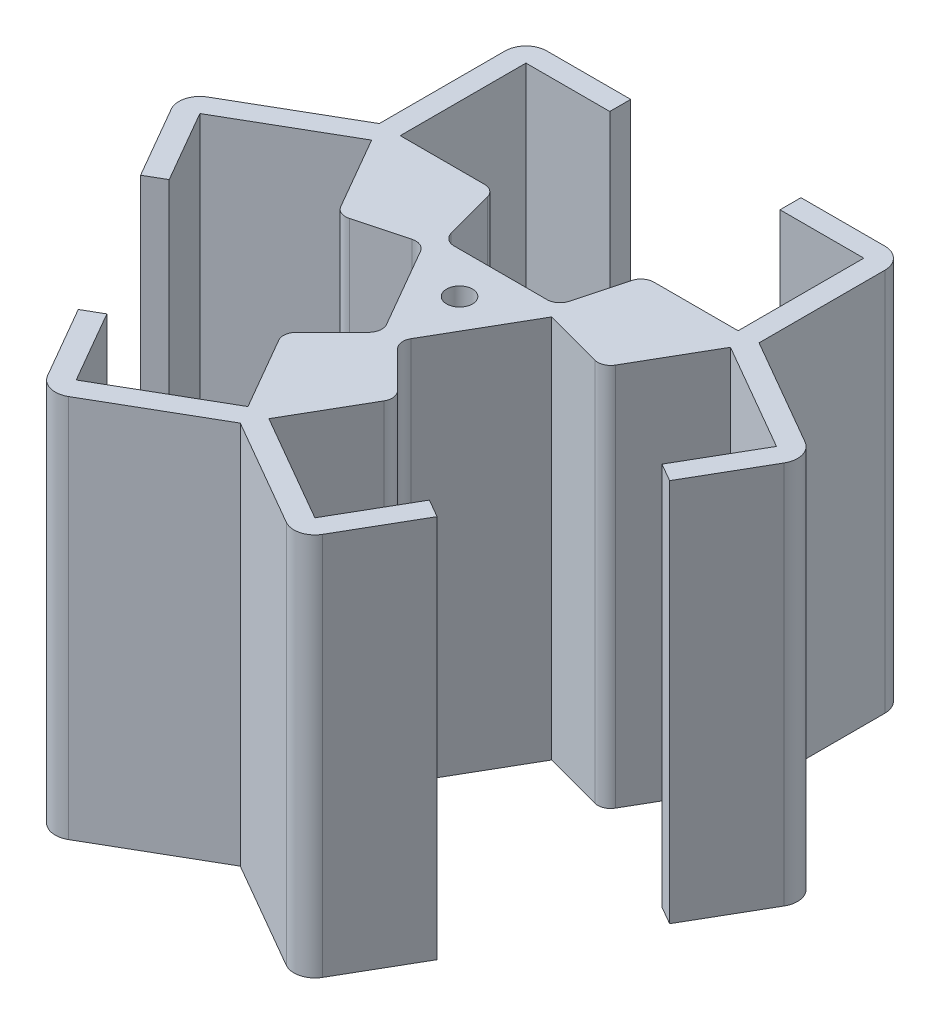
SolidWorks part; units mm, degrees
ref_plane "Alzado" through (0, 0, 0) normal (0, 0, 1) x (1, 0, 0)
ref_plane "Planta" through (0, 0, 0) normal (0, 1, 0) x (1, 0, 0)
ref_plane "Vista lateral" through (0, 0, 0) normal (1, 0, 0) x (0, 0, -1)
sketch "Croquis1" plane through (0, 0, 0) normal (0, 1, 0) x (1, 0, 0)
  line L0 (0, 50.8) -> (0, -50.8) construction
  line L1 (-50.8, 0) -> (50.8, 0) construction
  line L2 (0, 0) -> (-35.921, -35.921) construction
  line L3 (0, 0) -> (35.921, -35.921) construction
  line L10 (0, -17.5) -> (-15.1554, 8.75) construction
  line L11 (-15.1554, 8.75) -> (15.1554, 8.75) construction
  line L12 (15.1554, 8.75) -> (0, -17.5) construction
  line L13 (-1.2978, -16.7522) -> (-15.1813, 7.2027) construction
  line L14 (1.2978, -16.7522) -> (15.1813, 7.2027) construction
  line L15 (-13.8835, 9.4549) -> (13.8835, 9.4549) construction
  line L16 (1.6964, -16.0645) -> (13.335, -27.7031)
  line L17 (13.335, -27.7031) -> (0, -50.8)
  line L18 (0, -50.8) -> (-13.335, -27.7031)
  line L19 (-13.335, -27.7031) -> (-1.6964, -16.0645)
  line L20 (-17.3241, 25.4) -> (-13.0641, 9.5013)
  line L21 (-43.9941, 25.4) -> (-17.3241, 25.4)
  line L22 (-30.6591, 2.3031) -> (-43.9941, 25.4)
  line L23 (-14.7604, 6.5631) -> (-30.6591, 2.3031)
  line L24 (30.6591, 2.3031) -> (14.7604, 6.5631)
  line L25 (43.9941, 25.4) -> (30.6591, 2.3031)
  line L26 (17.3241, 25.4) -> (43.9941, 25.4)
  line L27 (13.0641, 9.5013) -> (17.3241, 25.4)
  line L28 (-14.7604, 6.5631) -> (-1.6964, -16.0645)
  line L29 (1.6964, -16.0645) -> (14.7604, 6.5631)
  line L30 (-13.0641, 9.5013) -> (13.0641, 9.5013)
  line L31 (-43.9941, 25.4) -> (0, -50.8) construction
  line L32 (43.9941, 25.4) -> (0, -50.8) construction
  line L33 (-43.9941, 25.4) -> (43.9941, 25.4) construction
  circle A0 centre (0, 0) radius 50.8 construction
  circle A7 centre (0, 0) radius 17.5 construction
  circle A8 centre (-13.8835, 7.9549) radius 1.5 construction
  circle A9 centre (13.8835, 7.9549) radius 1.5 construction
  circle A10 centre (0, -16) radius 1.5 construction
  arc A11 (-15.1813, 7.2027) -> (-13.8835, 9.4549) centre (-13.8835, 7.9549) cw construction
  arc A12 (15.1813, 7.2027) -> (13.8835, 9.4549) centre (13.8835, 7.9549) ccw construction
  arc A13 (1.2978, -16.7522) -> (-1.2978, -16.7522) centre (0, -16) cw construction
  arc A14 (-15.1813, 7.2027) -> (-13.8835, 9.4549) centre (-13.8835, 7.9549) cw construction
  arc A15 (13.8835, 9.4549) -> (15.1813, 7.2027) centre (13.8835, 7.9549) cw construction
  arc A16 (-1.2978, -16.7522) -> (1.2978, -16.7522) centre (0, -16) ccw construction
  circle A17 centre (0, 0) radius 76.2 construction
  point P45 (0, 0)
  dimension "D1" = 101.6
  dimension "D6" = 13.8835
  dimension "D9" = 3
  dimension "D5" = 3
  dimension "D4" = 35
  dimension "D10" = 152.4
  dimension "D2" = 45
  dimension "D3" = 45
  dimension "D7" = 26.67
extrude "Saliente-Extruir1" add sketch "Croquis1" along normal blind 88.9
sketch "Croquis4" plane through (0, 88.9, 0) normal (0, 1, 0) x (1, 0, 0)
  circle A0 centre (0, 0) radius 3
  dimension "D1" = 6
extrude "Cortar-Extruir1" cut sketch "Croquis4" against normal through all
fillet "Redondeo6" radius 3 5 edges at (-14.7604, 44.45, -6.5631) (1.6964, 44.45, 16.0645) (-1.6964, 44.45, 16.0645) (-13.0641, 44.45, -9.5013) (13.0641, 44.45, -9.5013)
fillet "Redondeo7" radius 3 6 edges at (-17.3241, 44.45, -25.4) (-30.6591, 44.45, -2.3031) (17.3241, 44.45, -25.4) (-13.335, 44.45, 27.7031) (30.6591, 44.45, -2.3031) (13.335, 44.45, 27.7031)
scale "Escala2" scale about centroid uniform scaling yes scale factor 1.03
sketch "Croquis12" plane through (0, 91.1225, 0) normal (0, 1, 0) x (1, 0, 0)
  circle A0 centre (0, 0) radius 76.2 construction
  circle A1 centre (0, 0) radius 101.6 construction
  dimension "D1" = 152.4
  dimension "D2" = 203.2
sketch "Croquis17" plane through (0, 90.2335, 0) normal (0, 1, 0) x (1, 0, 0)
  line L0 (-45.3137, 26.1621) -> (-45.3137, 56.1621)
  line L1 (-40.3137, 61.1621) -> (-20.3137, 61.1621)
  line L2 (-20.3137, 61.1621) -> (-20.3137, 56.1621)
  line L3 (-20.3137, 56.1621) -> (-40.3137, 56.1621)
  line L4 (-40.3137, 56.1621) -> (-40.3137, 26.1621)
  line L5 (-20.2146, 26.1621) -> (-45.3137, 26.1621) construction
  line L6 (-40.3137, 26.1621) -> (-45.3137, 26.1621)
  line L7 (0, 76.2) -> (0, -76.2) construction
  line L8 (76.2, 0) -> (-76.2, 0) construction
  line L9 (40.3137, 56.1621) -> (40.3137, 26.1621)
  line L10 (20.3137, 56.1621) -> (40.3137, 56.1621)
  line L11 (20.3137, 61.1621) -> (20.3137, 56.1621)
  line L12 (40.3137, 61.1621) -> (20.3137, 61.1621)
  line L13 (45.3137, 26.1621) -> (45.3137, 56.1621)
  line L14 (40.3137, 26.1621) -> (45.3137, 26.1621)
  line L15 (42.814, 21.832) -> (45.314, 26.1621)
  line L16 (45.314, 26.1621) -> (71.2947, 11.1621)
  line L17 (73.1248, 4.332) -> (63.1248, -12.9885)
  line L18 (63.1248, -12.9885) -> (58.7947, -10.4885)
  line L19 (58.7947, -10.4885) -> (68.7947, 6.832)
  line L20 (68.7947, 6.832) -> (42.814, 21.832)
  line L21 (28.481, -62.9934) -> (2.5003, -47.9934)
  line L22 (2.5003, -47.9934) -> (0.0003, -52.3235)
  line L23 (0.0003, -52.3235) -> (25.981, -67.3235)
  line L24 (32.8112, -65.4934) -> (42.8112, -48.1728)
  line L25 (42.8112, -48.1728) -> (38.481, -45.6728)
  line L26 (38.481, -45.6728) -> (28.481, -62.9934)
  line L27 (-2.4999, -47.9936) -> (0.0001, -52.3237)
  line L28 (0.0001, -52.3237) -> (-25.9806, -67.3237)
  line L29 (-32.8107, -65.4936) -> (-42.8107, -48.1731)
  line L30 (-42.8107, -48.1731) -> (-38.4806, -45.6731)
  line L31 (-38.4806, -45.6731) -> (-28.4806, -62.9936)
  line L32 (-28.4806, -62.9936) -> (-2.4999, -47.9936)
  line L33 (-68.7943, 6.8317) -> (-42.8135, 21.8317)
  line L34 (-42.8135, 21.8317) -> (-45.3135, 26.1619)
  line L35 (-45.3135, 26.1619) -> (-71.2943, 11.1619)
  line L36 (-73.1244, 4.3317) -> (-63.1244, -12.9888)
  line L37 (-63.1244, -12.9888) -> (-58.7943, -10.4888)
  line L38 (-58.7943, -10.4888) -> (-68.7943, 6.8317)
  line L39 (-45.3137, 26.1621) -> (-32.7641, 4.4257) construction
  arc A0 (-45.3137, 56.1621) -> (-40.3137, 61.1621) centre (-40.3137, 56.1621) cw
  circle A2 centre (0, 0) radius 76.2 construction
  arc A3 (45.3137, 56.1621) -> (40.3137, 61.1621) centre (40.3137, 56.1621) ccw
  arc A4 (71.2947, 11.1621) -> (73.1248, 4.332) centre (68.7947, 6.832) cw
  arc A5 (25.981, -67.3235) -> (32.8112, -65.4934) centre (28.481, -62.9934) ccw
  arc A6 (-25.9806, -67.3237) -> (-32.8107, -65.4936) centre (-28.4806, -62.9936) cw
  arc A7 (-71.2943, 11.1619) -> (-73.1244, 4.3317) centre (-68.7943, 6.8317) ccw
  point P55 (0.0001, 0.0002)
  dimension "D1" = 5
  dimension "D3" = 30
  dimension "D2" = 20
  dimension "D5" = 0.0001
  dimension "D4" = 3
extrude "Saliente-Extruir2" add sketch "Croquis17" against normal through all
